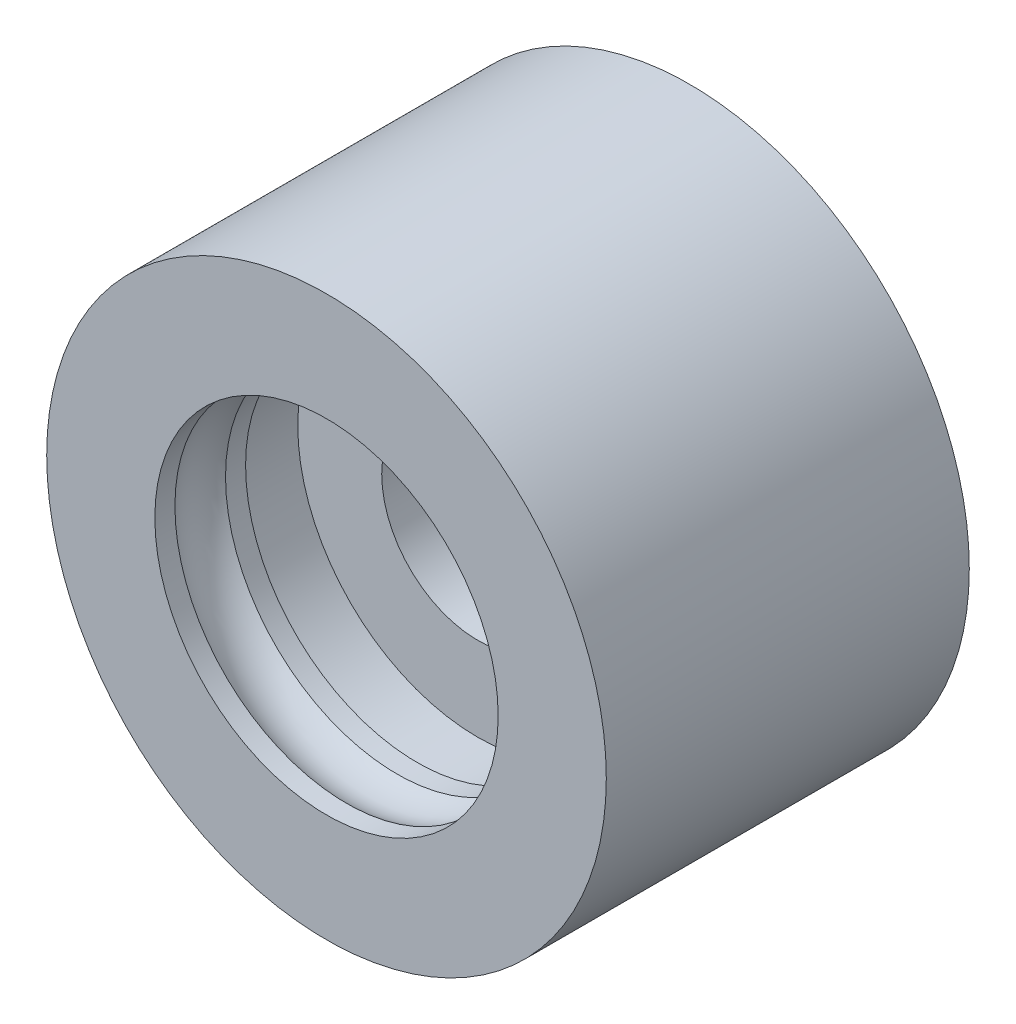
SolidWorks part; units mm, degrees
material "Titanium"
ref_plane "Front Plane" through (0, 0, 0) normal (0, 0, 1) x (1, 0, 0)
ref_plane "Top Plane" through (0, 0, 0) normal (0, 1, 0) x (1, 0, 0)
ref_plane "Right Plane" through (0, 0, 0) normal (1, 0, 0) x (0, 0, -1)
sketch "Sketch1" plane through (0, 0, 0) normal (0, 0, 1) x (1, 0, 0)
  circle A0 centre (0, 0) radius 5.95 construction
  circle A1 centre (0, 0) radius 9.25
  dimension "D1" = 11.9
  dimension "D2" = 18.5
extrude "Boss-Extrude1" add sketch "Sketch1" along normal blind 12
sketch "Sketch2" plane through (0, 0, 0) normal (0, 0, -1) x (-1, 0, 0)
  circle A0 centre (0, 0) radius 5.95
  dimension "D1" = 11.9
extrude "Cut-Extrude1" cut sketch "Sketch2" against normal blind 4
sketch "Sketch4" plane through (0, 0, 0) normal (0, 0, -1) x (-1, 0, 0)
  line L0 (1, 5.8654) -> (1, 8.8654)
  line L1 (1, 8.8654) -> (-1, 8.8654)
  line L2 (-1, 8.8654) -> (-1, 5.8654)
  circle A0 centre (0, 0) radius 5.95 construction
  circle A1 centre (0, 0) radius 5.95 construction
  arc A2 (1, 5.8654) -> (-1, 5.8654) centre (0, 0) ccw
  dimension "D1" = 2
  dimension "D2" = 3
extrude "Cut-Extrude2" cut sketch "Sketch4" against normal blind 3
pattern_circular "CirPattern1" count 8 over 360 about axis through (0, 0, 0) along (0, 0, 1) of "Cut-Extrude2"
sketch "Sketch5" plane through (0, 0, 12) normal (0, 0, 1) x (1, 0, 0)
  circle A0 centre (0, 0) radius 3.175
  dimension "D1" = 6.35
extrude "Cut-Extrude3" cut sketch "Sketch5" against normal up to surface (8 mm away) up to face at (-5.95, 0, 4)
sketch "Sketch6" plane through (0, 0, 12) normal (0, 0, 1) x (1, 0, 0)
  circle A0 centre (0, 0) radius 5.95 construction
  circle A1 centre (0, 0) radius 5.95
extrude "Cut-Extrude4" cut sketch "Sketch6" against normal offset from surface (2 mm away) 3 from offset 3 up to face at (-3.175, 0, 4) offset against normal yes
sketch "Sketch7" plane through (0, 0, 12) normal (0, 0, 1) x (1, 0, 0)
  circle A0 centre (0, 0) radius 5.675
  dimension "D1" = 11.35
extrude "Cut-Extrude5" cut sketch "Sketch7" against normal up to next
sketch "Sketch8" plane through (0, 0, 0) normal (0, 1, 0) x (1, 0, 0)
  line L0 (-5.675, -12) -> (5.675, -12) construction
  line L1 (-5.93, -10.5) -> (-5.93, -12) construction
  line L2 (-9.25, -12) -> (9.25, -12) construction
  line L3 (0, 0) -> (0, -12) construction
  line L6 (1, 0) -> (-1, 0) construction
  circle A0 centre (-4.43, -10.5) radius 1.5
  dimension "D1" = 3
  dimension "D2" = 5.93
revolve "Cut-Revolve1" cut sketch "Sketch8" angle 360 about L3
fillet "Fillet1" radius 1 16 edges at (4.8545, 3.4403, 1.5) (5.8654, -1, 1.5) (4.8545, -3.4403, 1.5) (1, -5.8654, 1.5) (-1, -5.8654, 1.5) (3.4403, -4.8545, 1.5) (5.8654, 1, 1.5) (3.4403, 4.8545, 1.5) (1, 5.8654, 1.5) (-1, 5.8654, 1.5) (-3.4403, 4.8545, 1.5) (-4.8545, 3.4403, 1.5) (-3.4403, -4.8545, 1.5) (-4.8545, -3.4403, 1.5) (-5.8654, -1, 1.5) (-5.8654, 1, 1.5)
